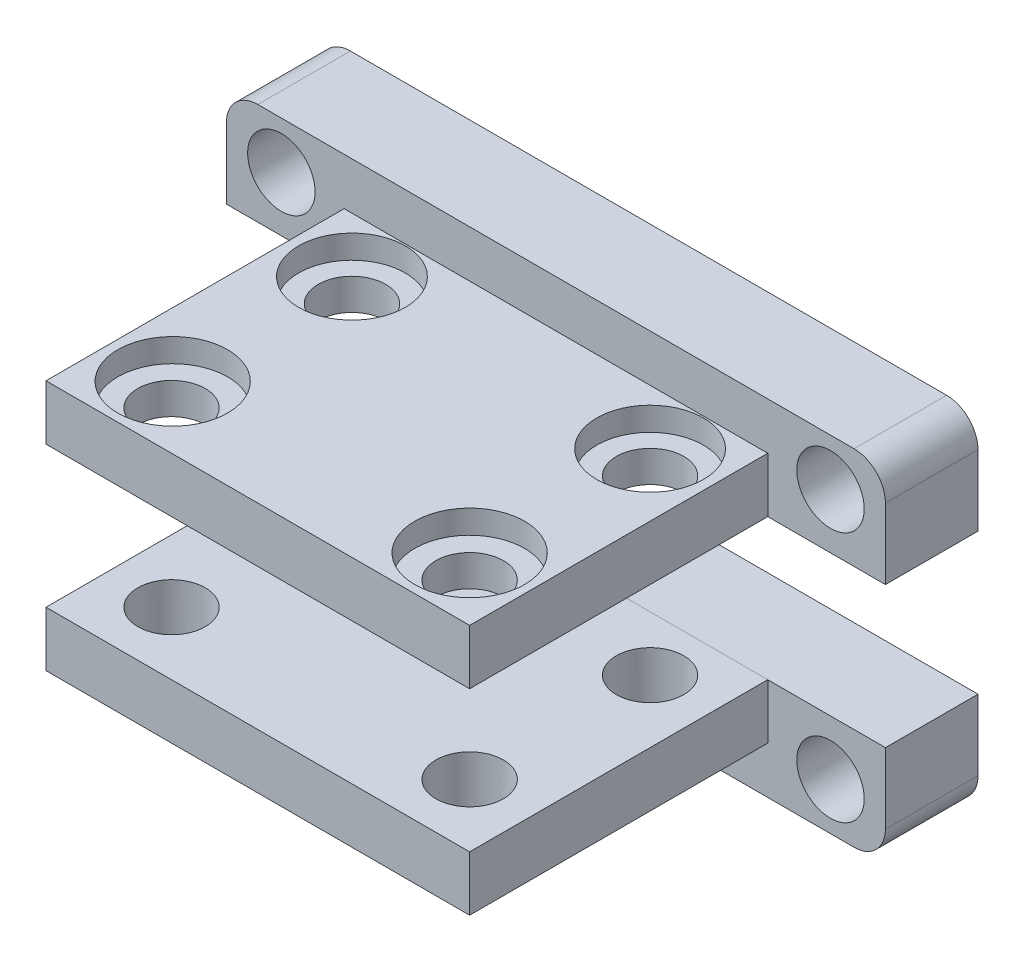
SolidWorks part; units mm, degrees
material "PEI"
ref_plane "前视基准面" through (0, 0, 0) normal (0, 0, 1) x (1, 0, 0)
ref_plane "上视基准面" through (0, 0, 0) normal (0, 1, 0) x (1, 0, 0)
ref_plane "右视基准面" through (0, 0, 0) normal (1, 0, 0) x (0, 0, -1)
other "Configuration Table"
sketch "草图1" plane through (0, 0, 0) normal (0, 0, 1) x (1, 0, 0)
  line L1 (-21, 11) -> (21, 11)
  line L2 (-21, 11) -> (-21, -11)
  line L3 (-21, -11) -> (21, -11)
  line L4 (21, 11) -> (21, -11)
  line L5 (-21, 11) -> (21, -11) construction
  line L6 (-21, -11) -> (21, 11) construction
  point P0 (0, 0)
  dimension "D1" = 42
  dimension "D2" = 22
extrude "凸台-拉伸1" add sketch "草图1" along normal blind 5.9
fillet "圆角1" radius 2 4 edges at (21, -11, 2.95) (-21, -11, 2.95) (21, 11, 2.95) (-21, 11, 2.95)
sketch "草图2" plane through (0, 0, 5.9) normal (0, 0, 1) x (1, 0, 0)
  line L0 (19, 11) -> (-19, 11) construction
  line L1 (21, -9) -> (21, 9) construction
  line L2 (0, 0) -> (0, 21.9095) construction
  line L3 (0, 0) -> (27.0857, 0) construction
  circle A0 centre (17.5, 8) radius 2.15
  circle A2 centre (-17.5, 8) radius 2.15
  circle A3 centre (17.5, -8) radius 2.15
  circle A4 centre (-17.5, -8) radius 2.15
  dimension "D1" = 3
  dimension "4.3" = 4.3
  dimension "D2" = 3.5
extrude "切除-拉伸1" cut sketch "草图2" against normal blind 10
ref_plane "基准面1" through (0, 0, 24.9) normal (0, 0, -1) x (-1, 0, 0)
sketch "草图3" plane through (0, 0, 24.9) normal (0, 0, -1) x (-1, 0, 0)
  line L0 (-21, -9) -> (-21, 9) construction
  line L1 (19, -11) -> (-19, -11) construction
  line L2 (-19, 11) -> (19, 11) construction
  line L3 (21, 9) -> (21, -9) construction
  line L4 (-21, -4.5) -> (-21, 4.5)
  line L5 (13.5, -11) -> (-13.5, -11)
  line L6 (-13.5, 11) -> (13.5, 11)
  line L7 (21, 4.5) -> (21, -4.5)
  line L8 (0, 0) -> (0, 9) construction
  line L9 (0, 0) -> (7.0344, 0) construction
  line L10 (-13.5, 4.5) -> (-21, 4.5)
  line L11 (-13.5, 4.5) -> (-13.5, 11)
  line L12 (13.5, 4.5) -> (21, 4.5)
  line L13 (13.5, 4.5) -> (13.5, 11)
  line L14 (13.5, -4.5) -> (21, -4.5)
  line L15 (13.5, -4.5) -> (13.5, -11)
  line L16 (-13.5, -4.5) -> (-13.5, -11)
  line L17 (-13.5, -4.5) -> (-21, -4.5)
extrude "凸台-拉伸2" add sketch "草图3" along direction (0, 0, 1) on the side of the normal blind 19 separate body
sketch "草图4" plane through (0, 0, 24.9) normal (0, 0, 1) x (1, 0, 0)
  line L0 (21, 4.5) -> (21, -4.5) construction
  line L1 (-21, -4.5) -> (21, -4.5)
  line L2 (-21, -4.5) -> (-21, 4.5)
  line L3 (-21, 4.5) -> (21, 4.5)
  line L4 (21, -4.5) -> (21, 4.5)
  line L5 (-21, -4.5) -> (21, 4.5) construction
  line L6 (-21, 4.5) -> (21, -4.5) construction
  point P0 (0, 0)
  dimension "D1" = 9
extrude "切除-拉伸6" cut sketch "草图4" along direction (0, 0, 1) on the side against the normal blind 24.9
sketch "草图6" plane through (13.5, 0, 0) normal (1, 0, 0) x (0, 0, -1)
  line L0 (-24.9, 11) -> (-24.9, 8)
  line L1 (-24.9, 11) -> (-24.9, 4.5) construction
  line L2 (-5.9, 11) -> (-5.9, 8)
  line L3 (-5.9, 4.5) -> (-5.9, 9) construction
  line L4 (-24.9, 11) -> (-24.9, 4.5)
  line L5 (-24.9, 4.5) -> (-5.9, 4.5)
  line L6 (-5.9, 4.5) -> (-5.9, 11)
  line L7 (-5.9, 11) -> (-24.9, 11)
  line L11 (-5.9, 11) -> (-24.9, 11)
  line L12 (-5.9, 8) -> (-24.9, 8)
  line L13 (0, 0) -> (-13.4651, 0) construction
  line L14 (-5.9, -11) -> (-5.9, -8)
  line L15 (-5.9, -11) -> (-24.9, -11)
  line L16 (-24.9, -11) -> (-24.9, -8)
  line L17 (-5.9, -8) -> (-24.9, -8)
  dimension "D1" = 0
extrude "切除-拉伸7" cut sketch "草图6" along direction (1, 0, 0) on the side against the normal up to next (27 mm away)
sketch "草图7" plane through (0, 8, 0) normal (0, 1, 0) x (1, 0, 0)
  line L0 (-13.5, -5.9) -> (-13.5, -24.9) construction
  line L1 (-13.5, -5.9) -> (13.5, -5.9) construction
  line L2 (19, -5.9) -> (-19, -5.9) construction
  line L3 (0, 0) -> (0, -20.1101) construction
  circle A0 centre (-9.5, -9.4) radius 2.15
  circle A1 centre (9.5, -9.4) radius 2.15
  circle A2 centre (-9.5, -20.9) radius 2.15
  circle A3 centre (9.5, -20.9) radius 2.15
  dimension "D1" = 4
  dimension "D3" = 4.3
  dimension "D2" = 3.5
  dimension "D4" = 15
extrude "切除-拉伸8" cut sketch "草图7" against normal blind 50
sketch "草图8" plane through (0, 8, 0) normal (0, 1, 0) x (1, 0, 0)
  circle A0 centre (-9.5, -9.4) radius 3.4
  circle A1 centre (9.5, -9.4) radius 3.4
  circle A2 centre (-9.4307, -20.8953) radius 3.5
  circle A3 centre (9.5, -20.9) radius 3.5
  dimension "D1" = 6.8
extrude "切除-拉伸11" cut sketch "草图8" against normal blind 1.5
